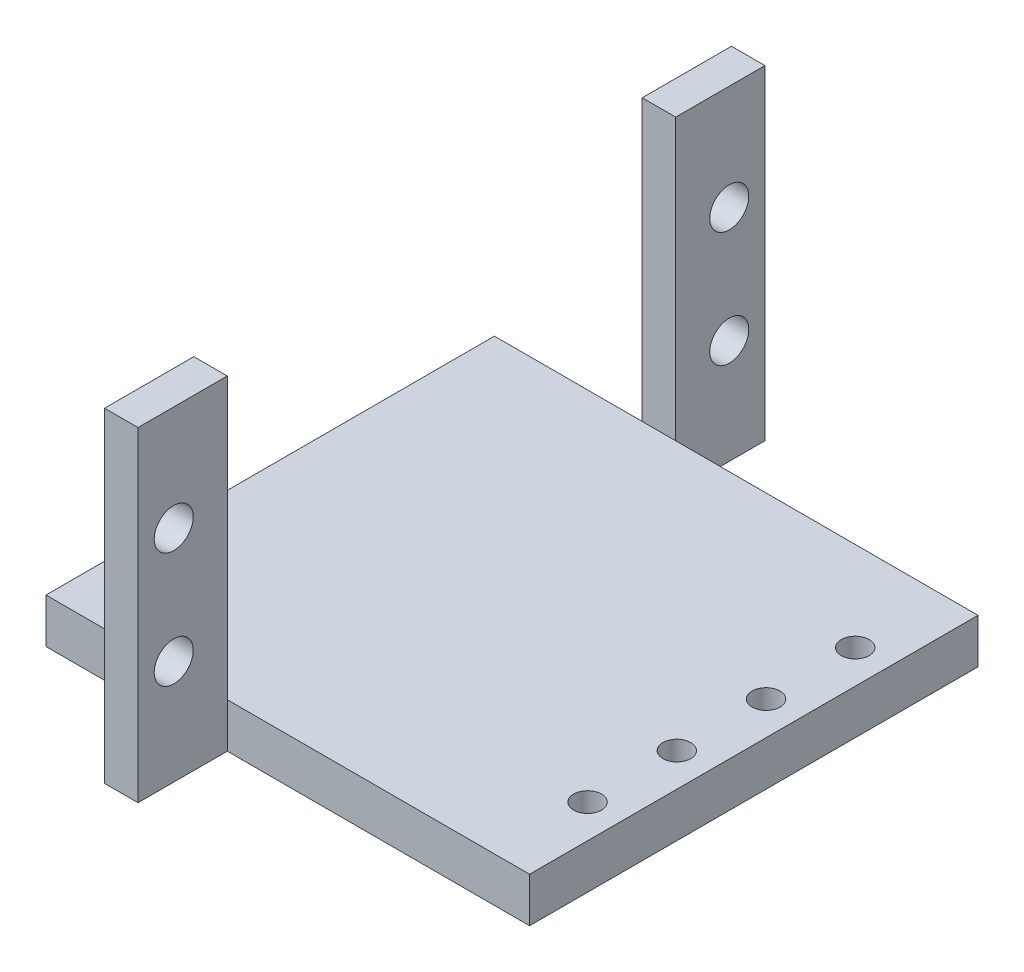
SolidWorks part; units mm, degrees
ref_plane "Front Plane" through (0, 0, 0) normal (0, 0, 1) x (1, 0, 0)
ref_plane "Top Plane" through (0, 0, 0) normal (0, 1, 0) x (1, 0, 0)
ref_plane "Right Plane" through (0, 0, 0) normal (1, 0, 0) x (0, 0, -1)
sketch "Sketch23" plane through (0, 0, 0) normal (0, 1, 0) x (1, 0, 0)
  line L0 (-77.0747, 0) -> (-63.8247, 0)
  line L1 (-63.8247, 0) -> (-63.8247, -8)
  line L2 (-63.8247, -8) -> (-60.8247, -8)
  line L3 (-60.8247, -8) -> (-60.8247, 0)
  line L4 (-60.8247, 0) -> (-34.3747, 0)
  line L5 (-34.3747, 0) -> (-60.8247, 0) construction
  line L7 (-77.0747, 0) -> (-77.0747, 40.2)
  line L8 (-77.0747, 40.2) -> (-63.8247, 40.2)
  line L9 (-63.8247, 40.2) -> (-63.8247, 48.2)
  line L10 (-63.8247, 48.2) -> (-60.8247, 48.2)
  line L11 (-60.8247, 48.2) -> (-60.8247, 40.2)
  line L12 (-60.8247, 40.2) -> (-34.3747, 40.2)
  line L13 (-34.3747, 40.2) -> (-34.3747, 0)
  dimension "D1" = 13.25
extrude "Boss-Extrude2" add sketch "Sketch23" along normal blind 4 contours L9 L10 L11 L12 L13 L4 L3 L2 L1 L0 L7 L8
sketch "Sketch24" plane through (0, 4, 0) normal (0, 1, 0) x (1, 0, 0)
  line L0 (-60.8247, 48.2) -> (-63.8247, 48.2) construction
  line L1 (-60.8247, 0) -> (-63.8247, 0)
  line L2 (-60.8247, 0) -> (-60.8247, -8)
  line L3 (-60.8247, -8) -> (-63.8247, -8)
  line L4 (-63.8247, 0) -> (-63.8247, -8)
  line L5 (-60.8247, 40.2) -> (-63.8247, 40.2)
  line L6 (-60.8247, 40.2) -> (-60.8247, 48.2)
  line L7 (-60.8247, 48.2) -> (-63.8247, 48.2)
  line L8 (-63.8247, 40.2) -> (-63.8247, 48.2)
extrude "Boss-Extrude3" add sketch "Sketch24" along normal blind 25.13
sketch "Sketch25" plane through (-63.8247, 0, 0) normal (-1, 0, 0) x (0, 0, 1)
  line L0 (-40.2, 0) -> (-40.2, 4) construction
  line L1 (-40.2, 29.13) -> (-40.2, 4) construction
  line L2 (-40.2, 0) -> (-45, 0) construction
  line L3 (-48.2, 0) -> (-40.2, 0) construction
  line L5 (-40.2, 4) -> (7, 4) construction
  line L7 (7, 4) -> (0, 4) construction
  line L8 (0, 29.13) -> (0, 4) construction
  line L9 (0, 4) -> (4.8784, 4) construction
  line L10 (4.8784, 4) -> (4.8, 9.375) construction
  line L11 (4.8, 9.375) -> (4.8, 19.725) construction
  line L12 (-40.2, 0) -> (-45, 0) construction
  line L13 (4.8784, 4) -> (4.8, 9.375) construction
  line L14 (0, 4) -> (0, 0) construction
  line L15 (0, 0) -> (0, 4) construction
  line L16 (0, 4) -> (4.8784, 4) construction
  line L17 (4.8784, 4) -> (4.8, 9.375) construction
  line L21 (-45, 4) -> (-45, 9.375) construction
  circle A0 centre (4.8, 9.375) radius 1.75
  circle A1 centre (-45, 9.375) radius 1.75
  circle A2 centre (-45, 19.725) radius 1.75
  circle A3 centre (4.8, 19.725) radius 1.75
extrude "Cut-Extrude1" cut sketch "Sketch25" against normal blind 4
sketch "Sketch26" plane through (-34.3747, 0, 0) normal (1, 0, 0) x (0, 0, -1)
  line L1 (40.2, 0) -> (0, 0)
  line L2 (40.2, 0) -> (40.2, 4)
  line L3 (40.2, 4) -> (0, 4)
  line L4 (0, 0) -> (0, 4)
extrude "Boss-Extrude4" add sketch "Sketch26" along normal blind 0.65
sketch "Sketch27" plane through (0, 4, 0) normal (0, 1, 0) x (1, 0, 0)
  line L5 (-33.7247, 0) -> (-33.7247, 40.2) construction
  circle A0 centre (-36.7247, 32.192) radius 1.25
  circle A1 centre (-36.7247, 24.2) radius 1.25
  circle A2 centre (-36.7247, 16.2) radius 1.25
  circle A3 centre (-36.7247, 8.2) radius 1.25
extrude "Cut-Extrude2" cut sketch "Sketch27" against normal blind 5
